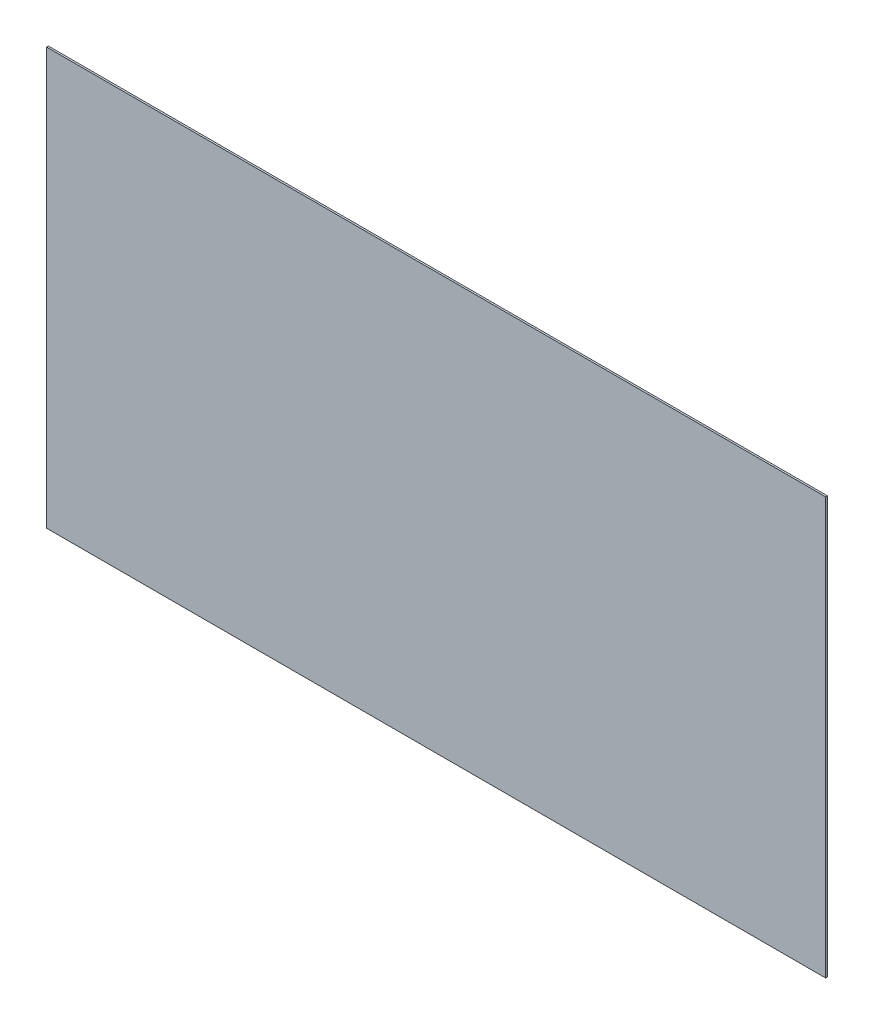
SolidWorks part; units mm, degrees
ref_plane "Front Plane" through (0, 0, 0) normal (0, 0, 1) x (1, 0, 0)
ref_plane "Top Plane" through (0, 0, 0) normal (0, 1, 0) x (1, 0, 0)
ref_plane "Right Plane" through (0, 0, 0) normal (1, 0, 0) x (0, 0, -1)
sketch "Sketch1" plane through (0, 0, 0) normal (0, 0, 1) x (1, 0, 0)
  line L1 (-21.5, -11.5) -> (21.5, -11.5)
  line L2 (-21.5, -11.5) -> (-21.5, 11.5)
  line L3 (-21.5, 11.5) -> (21.5, 11.5)
  line L4 (21.5, -11.5) -> (21.5, 11.5)
  line L5 (-21.5, -11.5) -> (21.5, 11.5) construction
  line L6 (-21.5, 11.5) -> (21.5, -11.5) construction
  point P0 (0, 0)
  dimension "D1" = 23
  dimension "D2" = 43
extrude "Boss-Extrude1" add sketch "Sketch1" along normal blind 0.1
